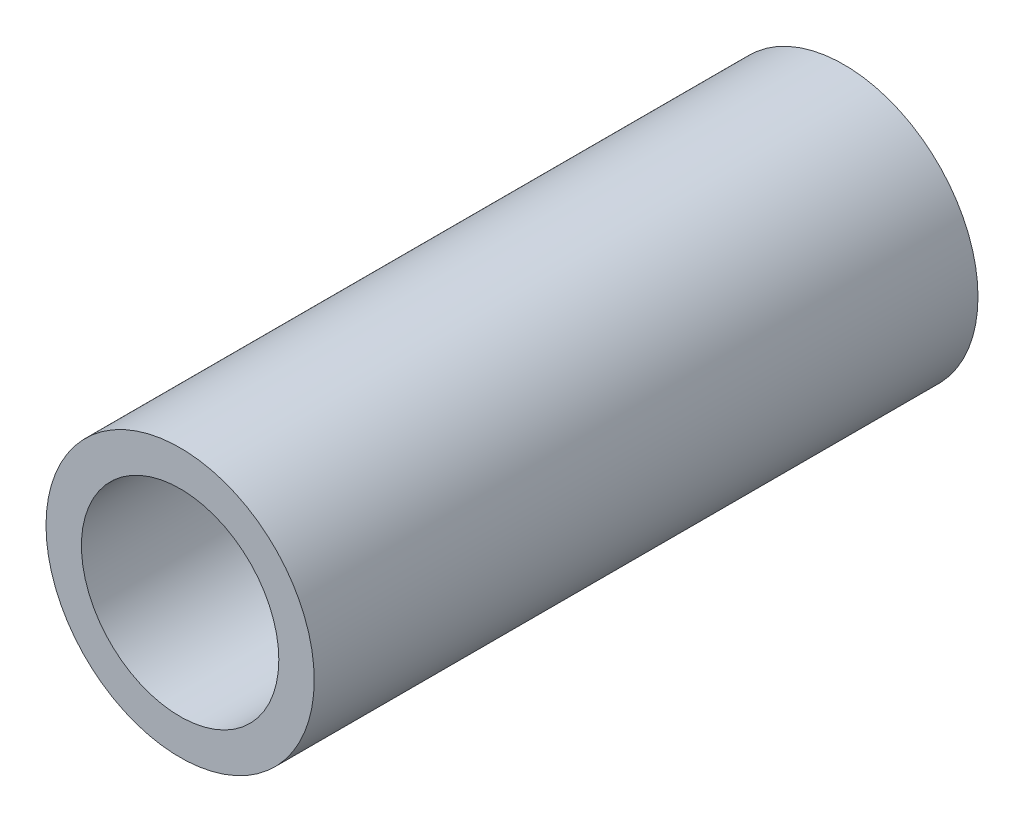
SolidWorks part; units mm, degrees
ref_plane "Front Plane" through (0, 0, 0) normal (0, 0, 1) x (1, 0, 0)
ref_plane "Top Plane" through (0, 0, 0) normal (0, 1, 0) x (1, 0, 0)
ref_plane "Right Plane" through (0, 0, 0) normal (1, 0, 0) x (0, 0, -1)
sketch "Sketch1" plane through (0, 0, 0) normal (0, 0, 1) x (1, 0, 0)
  circle A0 centre (0, 0) radius 4.0894
  circle A1 centre (0, 0) radius 5.5562
  dimension "D1" = 11.1125
  dimension "D2" = 8.1788
extrude "Boss-Extrude1" add sketch "Sketch1" along normal up to surface (27.5 mm away)
